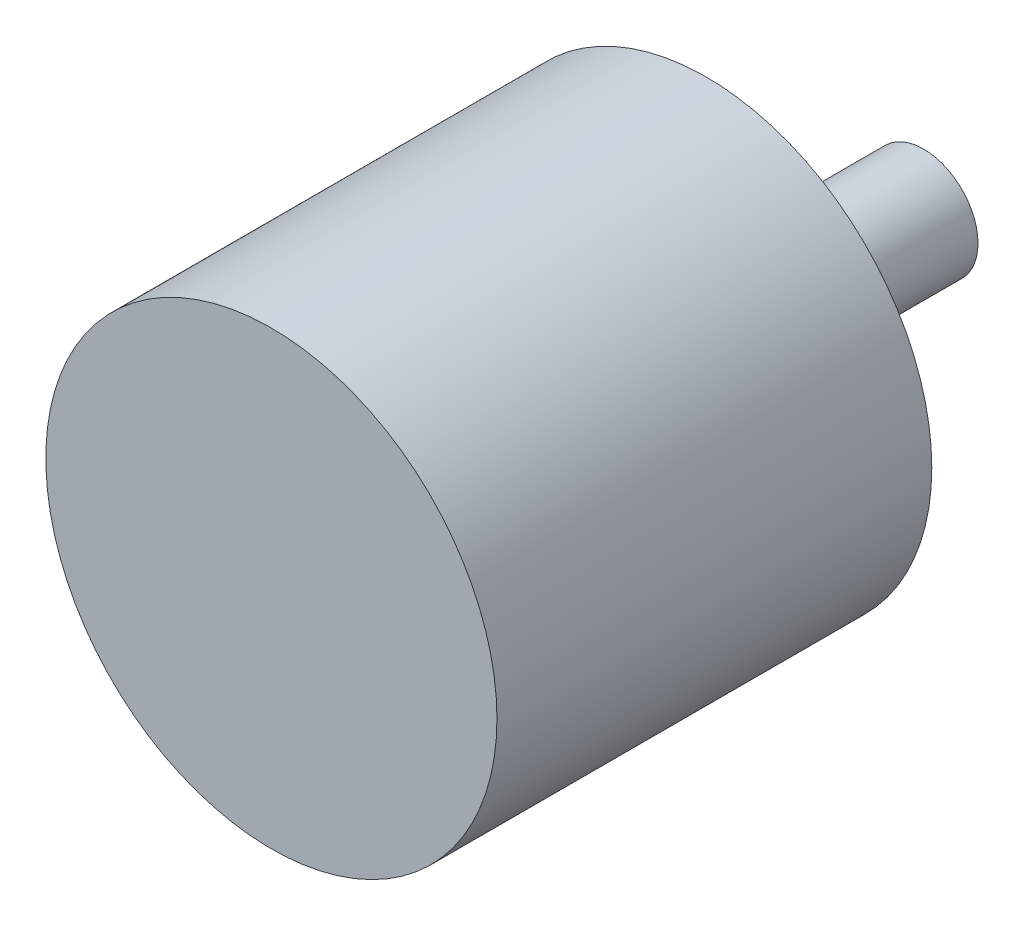
SolidWorks part; units mm, degrees
ref_plane "Front Plane" through (0, 0, 0) normal (0, 0, 1) x (1, 0, 0)
ref_plane "Top Plane" through (0, 0, 0) normal (0, 1, 0) x (1, 0, 0)
ref_plane "Right Plane" through (0, 0, 0) normal (1, 0, 0) x (0, 0, -1)
sketch "Sketch1" plane through (0, 0, 0) normal (0, 0, 1) x (1, 0, 0)
  circle A0 centre (0, 0) radius 0.5
  dimension "D1" = 1
extrude "Boss-Extrude1" add sketch "Sketch1" along normal blind 2
sketch "Sketch2" plane through (0, 0, 2) normal (0, 0, 1) x (1, 0, 0)
  circle A0 centre (0, 0) radius 2.075
  dimension "D1" = 4.15
extrude "Boss-Extrude2" add sketch "Sketch2" along normal blind 4
